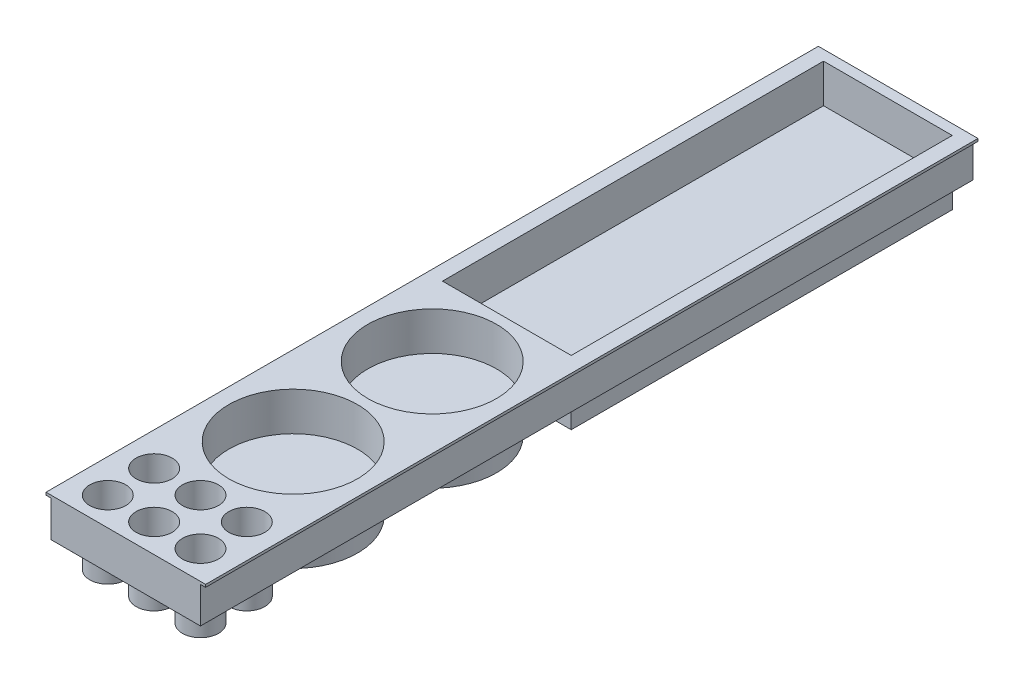
SolidWorks part; units mm, degrees
material "ABS"
ref_plane "Ön Düzlem" through (0, 0, 0) normal (0, 0, 1) x (1, 0, 0)
ref_plane "Üst Düzlem" through (0, 0, 0) normal (0, 1, 0) x (1, 0, 0)
ref_plane "Sağ Düzlem" through (0, 0, 0) normal (1, 0, 0) x (0, 0, -1)
sketch "Sketch1" plane through (0, 0, 0) normal (0, 1, 0) x (1, 0, 0)
  line L0 (-29, -193) -> (-25, -193) construction
  line L1 (-29, 78) -> (29, 78)
  line L2 (-29, 78) -> (-29, -222)
  line L3 (-29, -222) -> (29, -222)
  line L4 (29, 78) -> (29, -222)
  line L5 (-11, -193) -> (-7, -193) construction
  line L6 (7, -193) -> (11, -193) construction
  line L7 (25, -193) -> (29, -193) construction
  line L8 (0, 78) -> (0, 74) construction
  line L9 (-25, 74) -> (25, 74)
  line L10 (-25, 74) -> (-25, -74)
  line L11 (-25, -74) -> (25, -74)
  line L12 (25, 74) -> (25, -74)
  line L13 (0, -74) -> (0, -78) construction
  line L14 (0, -128) -> (0, -132) construction
  line L15 (0, -182) -> (0, -186) construction
  line L16 (0, -200) -> (0, -204) construction
  line L17 (0, -218) -> (0, -222) construction
  line L18 (-25, -103) -> (25, -103) construction
  line L19 (-25, -103) -> (-29, -103) construction
  circle A0 centre (-18, -193) radius 7
  circle A1 centre (0, -193) radius 7
  circle A2 centre (18, -193) radius 7
  circle A3 centre (-18, -211) radius 7
  circle A4 centre (0, -211) radius 7
  circle A5 centre (18, -211) radius 7
  circle A6 centre (0, -157) radius 25
  circle A7 centre (0, -103) radius 25
  point P25 (0, -222)
  point P46 (-25, 0)
  dimension "D1" = 14
  dimension "D2" = 50
  dimension "D3" = 300
extrude "Boss-Extrude1" add sketch "Sketch1" against normal blind 15
sketch "Sketch3" plane through (0, 0, 0) normal (0, 1, 0) x (1, 0, 0)
  line L4 (-29, 78) -> (-29, -222)
  line L5 (-29, -222) -> (29, -222)
  line L6 (29, -222) -> (29, 78)
  line L7 (29, 78) -> (-29, 78)
  line L9 (-29, -222) -> (29, -222)
  line L10 (29, -222) -> (29, 78)
  line L11 (29, 78) -> (-29, 78)
  line L12 (29, 78) -> (-29, 78)
  line L13 (29, -222) -> (29, 78)
  line L14 (-29, -222) -> (29, -222)
  line L15 (-29, 78) -> (-29, -222)
  line L16 (29, 78) -> (-29, 78)
  line L17 (29, -222) -> (29, 78)
  line L18 (-29, -222) -> (29, -222)
  line L20 (25, 74) -> (-25, 74)
  line L21 (-25, 74) -> (-25, -74)
  line L22 (-25, -74) -> (25, -74)
  line L23 (25, -74) -> (25, 74)
  line L24 (25, 74) -> (-25, 74)
  line L25 (-25, 74) -> (-25, -74)
  line L26 (-25, -74) -> (25, -74)
  line L27 (25, -74) -> (25, 74)
  circle A1 centre (18, -211) radius 7
  circle A2 centre (18, -211) radius 7
  circle A3 centre (0, -211) radius 7
  circle A4 centre (0, -211) radius 7
  circle A5 centre (-18, -211) radius 7
  circle A6 centre (-18, -211) radius 7
  circle A7 centre (18, -193) radius 7
  circle A8 centre (18, -193) radius 7
  circle A9 centre (0, -193) radius 7
  circle A10 centre (0, -193) radius 7
  circle A11 centre (-18, -193) radius 7
  circle A12 centre (-18, -193) radius 7
  circle A13 centre (0, -103) radius 25
  circle A14 centre (0, -103) radius 25
  circle A15 centre (0, -157) radius 25
  circle A16 centre (0, -157) radius 25
  line M21 (-25, -74) -> (-25, 74)
  line M22 (-25, 74) -> (25, 74)
  line M23 (25, 74) -> (25, -74)
  line M24 (25, -74) -> (-25, -74)
  circle M25 centre (0, -157) radius 25
  circle M26 centre (0, -103) radius 25
  circle M27 centre (18, -211) radius 7
  circle M28 centre (-18, -211) radius 7
  circle M29 centre (0, -211) radius 7
  circle M30 centre (18, -193) radius 7
  circle M31 centre (0, -193) radius 7
  circle M32 centre (-18, -193) radius 7
  dimension "D1" = 0
  dimension "D2" = 0
  dimension "D3" = 0
  dimension "D4" = 0
  dimension "D5" = 0
  dimension "D6" = 0
  dimension "D7" = 0
  dimension "D8" = 0
  dimension "D9" = 0
  dimension "D10" = 0
  dimension "D11" = 0
extrude "Boss-Extrude2" add sketch "Sketch3" against normal blind 10 from offset 15 separate body contours M21 M24 M23 M22 | M26 | M25 | M32 | M31 | M30 | M27 | M29 | M28 offset against normal yes
sketch "Sketch6" plane through (0, 0, 0) normal (0, 1, 0) x (1, 0, 0)
  line L0 (-29, -222) -> (29, -222) construction
  line L1 (-29, 78) -> (-31, 78)
  line L2 (-29, 78) -> (-29, -222)
  line L3 (-29, -222) -> (-31, -222)
  line L4 (-31, 78) -> (-31, -222)
  line L5 (-29, -222) -> (29, -222)
  line L6 (0, -1000) -> (0, 49000) construction
  line L7 (31, 78) -> (31, -222)
  line L8 (29, -222) -> (31, -222)
  line L9 (29, 78) -> (29, -222)
  line L10 (29, 78) -> (31, 78)
  dimension "D1" = 2
extrude "Boss-Extrude4" add sketch "Sketch6" against normal blind 1 contours L2 L3 L4 L1 | L7 L8 L9 L10
